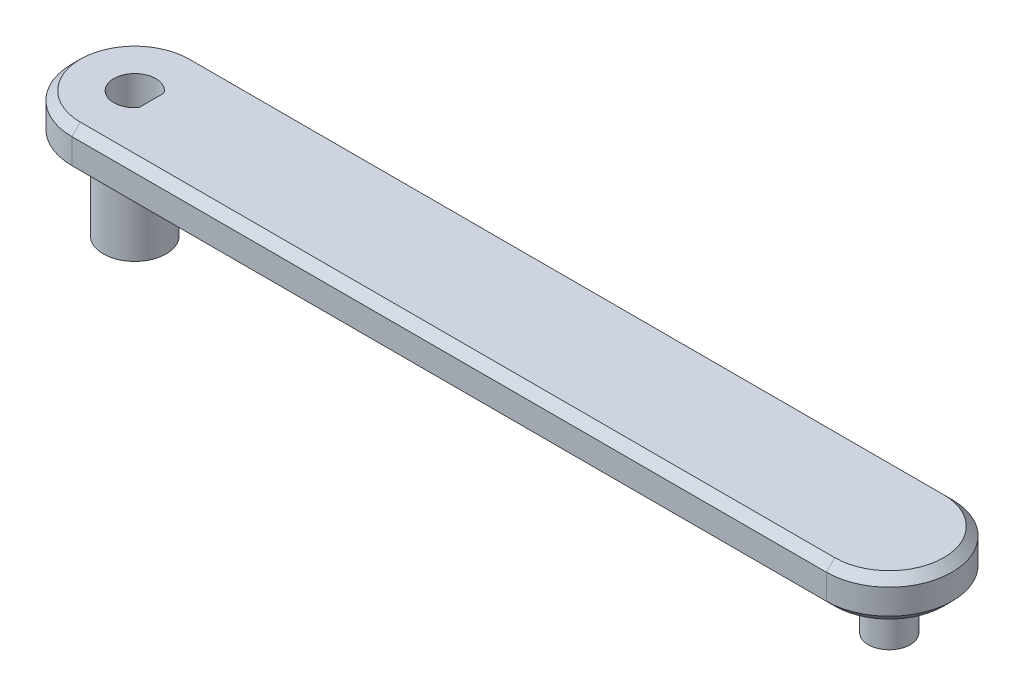
SolidWorks part; units mm, degrees
ref_plane "前视基准面" through (0, 0, 0) normal (0, 0, 1) x (1, 0, 0)
ref_plane "上视基准面" through (0, 0, 0) normal (0, 1, 0) x (1, 0, 0)
ref_plane "右视基准面" through (0, 0, 0) normal (1, 0, 0) x (0, 0, -1)
other "Configuration Table"
sketch "草图1" plane through (0, 0, 0) normal (0, 1, 0) x (1, 0, 0)
  line L0 (0, 0) -> (180, 0) construction
  line L1 (0, 15) -> (180, 15)
  line L2 (0, -15) -> (180, -15)
  arc A0 (0, 15) -> (0, -15) centre (0, 0) ccw
  arc A1 (180, -15) -> (180, 15) centre (180, 0) ccw
  circle A2 centre (180, 0) radius 5
  point P3 (90, 0)
  dimension "D2" = 15
  dimension "D3" = 10
  dimension "D1" = 180
extrude "凸台-拉伸2" add sketch "草图1" along normal blind 10 contours A1 L1 A0 L2
sketch "草图9" plane through (0, 0, 0) normal (0, -1, 0) x (1, 0, 0)
  circle A0 centre (0, 0) radius 7.5
  dimension "D1" = 15
chamfer "倒角1" distance 2 angle 45 8 edges at (-15, 10, 0) (90, 10, 15) (90, 10, -15) (195, 10, 0) (195, 0, 0) (90, 0, 15) (-15, 0, 0) (90, 0, -15)
sketch "草图4" plane through (0, 0, 0) normal (0, -1, 0) x (1, 0, 0)
  line L0 (4, 3) -> (4, -3)
  arc A0 (4, 3) -> (4, -3) centre (0, 0) ccw
  dimension "D1" = 10
  dimension "D2" = 4
extrude "凸台-拉伸7" add sketch "草图9" along normal blind 20
extrude "切除-拉伸3" cut sketch "草图4" against normal through all and the other way blind 24 contours A0 L0
sketch "草图11" plane through (0, 0, 0) normal (0, -1, 0) x (1, 0, 0)
  circle A0 centre (180, 0) radius 5
  dimension "D1" = 10
extrude "凸台-拉伸8" add sketch "草图11" along normal blind 12
